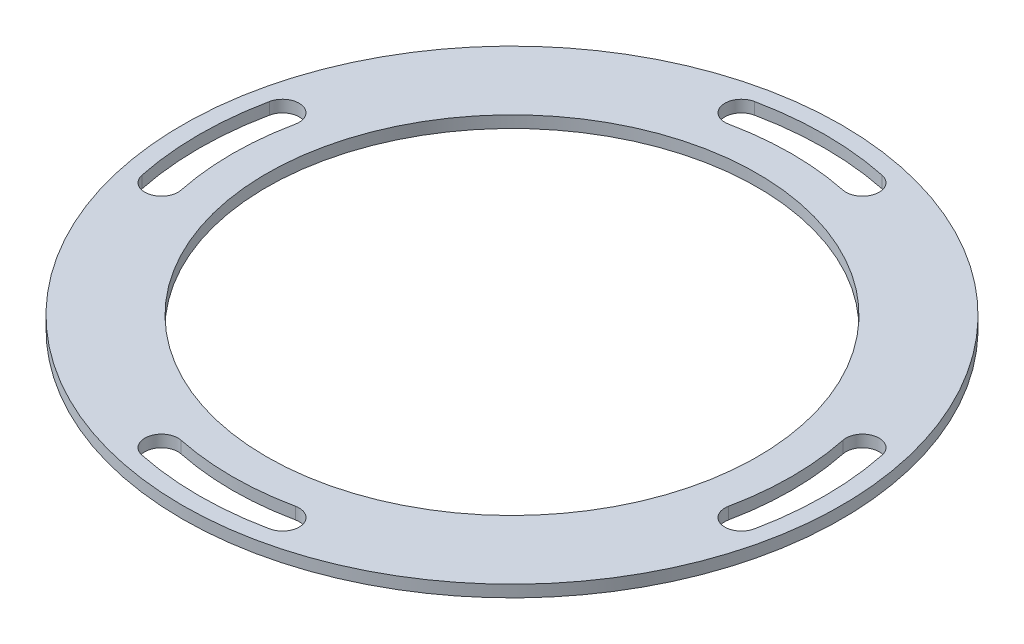
SolidWorks part; units mm, degrees
material "1.4301 (X5CrNi18-10)"
ref_plane "Piano frontale" through (0, 0, 0) normal (0, 0, 1) x (1, 0, 0)
ref_plane "Piano superiore" through (0, 0, 0) normal (0, 1, 0) x (1, 0, 0)
ref_plane "Piano destro" through (0, 0, 0) normal (1, 0, 0) x (0, 0, -1)
sketch "Schizzo1" plane through (0, 0, 0) normal (0, 1, 0) x (1, 0, 0)
  line L0 (0, 0) -> (-153.0828, 0) construction
  line L1 (0, 0) -> (-148.7698, 39.8628) construction
  line L2 (0, 0) -> (-148.7698, -39.8628) construction
  circle A0 centre (0, 0) radius 139
  circle A1 centre (0, 0) radius 103.5
  circle A2 centre (0, 0) radius 124.9564 construction
  arc A9 (-115.4685, 24.0987) -> (-129.1732, 26.9589) centre (-122.3208, 25.5288) ccw
  arc A10 (-115.4685, -24.0987) -> (-129.1732, -26.9589) centre (-122.3208, -25.5288) cw
  arc A11 (-115.4685, 24.0987) -> (-115.4685, -24.0987) centre (0, 0) ccw
  arc A14 (-129.1732, 26.9589) -> (-129.1732, -26.9589) centre (0, 0) ccw
  arc A16 (-24.0987, 115.4685) -> (-26.9589, 129.1732) centre (-25.5288, 122.3208) cw
  arc A17 (26.9589, 129.1732) -> (-26.9589, 129.1732) centre (0, 0) ccw
  arc A18 (24.0987, 115.4685) -> (26.9589, 129.1732) centre (25.5288, 122.3208) ccw
  arc A19 (24.0987, 115.4685) -> (-24.0987, 115.4685) centre (0, 0) ccw
  arc A20 (115.4685, 24.0987) -> (129.1732, 26.9589) centre (122.3208, 25.5288) cw
  arc A21 (129.1732, -26.9589) -> (129.1732, 26.9589) centre (0, 0) ccw
  arc A22 (115.4685, -24.0987) -> (129.1732, -26.9589) centre (122.3208, -25.5288) ccw
  arc A23 (115.4685, -24.0987) -> (115.4685, 24.0987) centre (0, 0) ccw
  arc A24 (24.0987, -115.4685) -> (26.9589, -129.1732) centre (25.5288, -122.3208) cw
  arc A25 (-26.9589, -129.1732) -> (26.9589, -129.1732) centre (0, 0) ccw
  arc A26 (-24.0987, -115.4685) -> (-26.9589, -129.1732) centre (-25.5288, -122.3208) ccw
  arc A27 (-24.0987, -115.4685) -> (24.0987, -115.4685) centre (0, 0) ccw
  point P17 (112.8023, 34.4871)
  point P24 (-0.0218, -0.0218)
  point P25 (126.1906, 38.5803)
  point P54 (0, 0)
  dimension "D2" = 15
  dimension "D5" = 4
extrude "Estrusione-Estrusione1" add sketch "Schizzo1" along normal mid plane 5
sketch "Schizzo4" plane through (0, -2.5, 0) normal (0, -1, 0) x (1, 0, 0)
  line L0 (0, -34.77) -> (0, 34.77) construction
  line L1 (30.8851, 0) -> (-30.8851, 0) construction
  point P4 (0, 0)
  point P8 (0, 0)
sketch "Schizzo5" plane through (0, 2.5, 0) normal (0, 1, 0) x (1, 0, 0)
  line L0 (0, 34.77) -> (0, -34.77) construction
  line L1 (0, 34.77) -> (0, -34.77) construction
  line L2 (30.8851, 0) -> (-30.8851, 0) construction
  line L3 (30.8851, 0) -> (-30.8851, 0) construction
